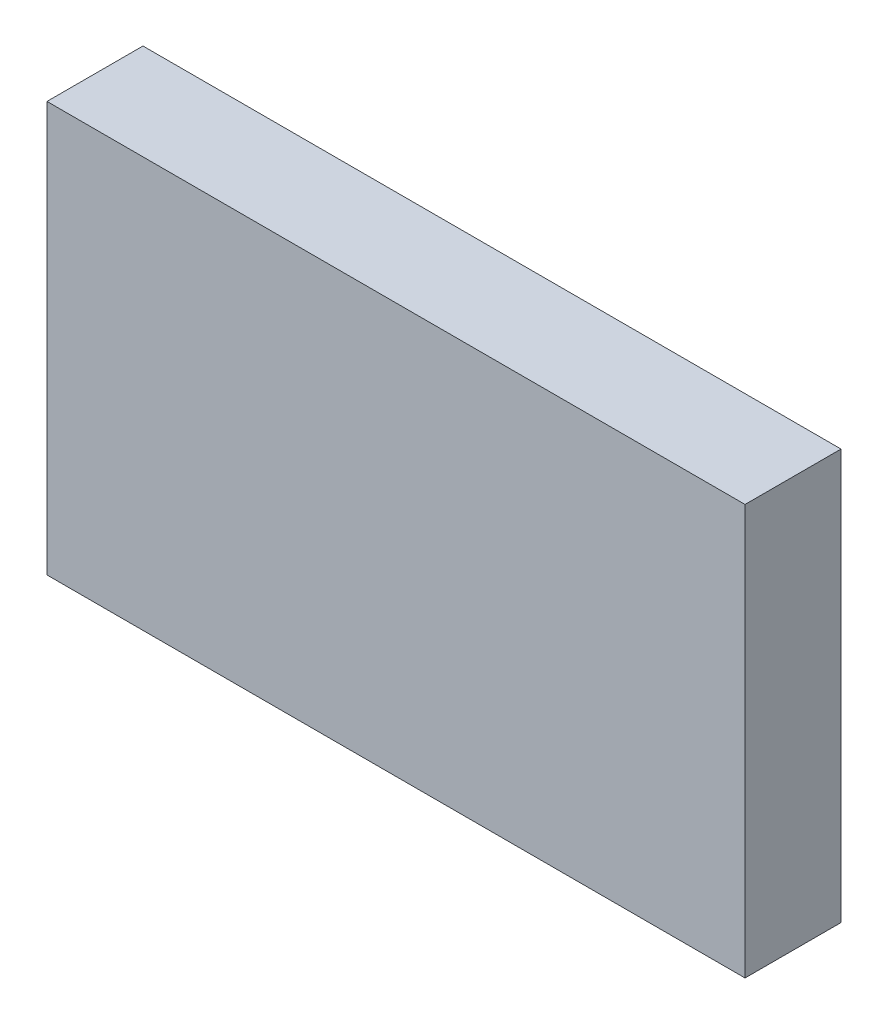
SolidWorks part; units mm, degrees
ref_plane "前视基准面" through (0, 0, 0) normal (0, 0, 1) x (1, 0, 0)
ref_plane "上视基准面" through (0, 0, 0) normal (0, 1, 0) x (1, 0, 0)
ref_plane "右视基准面" through (0, 0, 0) normal (1, 0, 0) x (0, 0, -1)
other "Configuration Table"
sketch "草图1" plane through (0, 0, 0) normal (0, 0, 1) x (1, 0, 0)
  line L6 (-16, -9.4) -> (16, -9.4)
  line L11 (-16, -9.4) -> (-16, 9.4)
  line L12 (-16, 9.4) -> (16, 9.4)
  line L13 (16, -9.4) -> (16, 9.4)
  line L14 (-16, -9.4) -> (16, 9.4) construction
  line L15 (-16, 9.4) -> (16, -9.4) construction
  point P0 (0, 0)
  point P5 (0, 0)
  dimension "D1" = 18.8
  dimension "D2" = 32
extrude "凸台-拉伸1" add sketch "草图1" along normal blind 4.4
